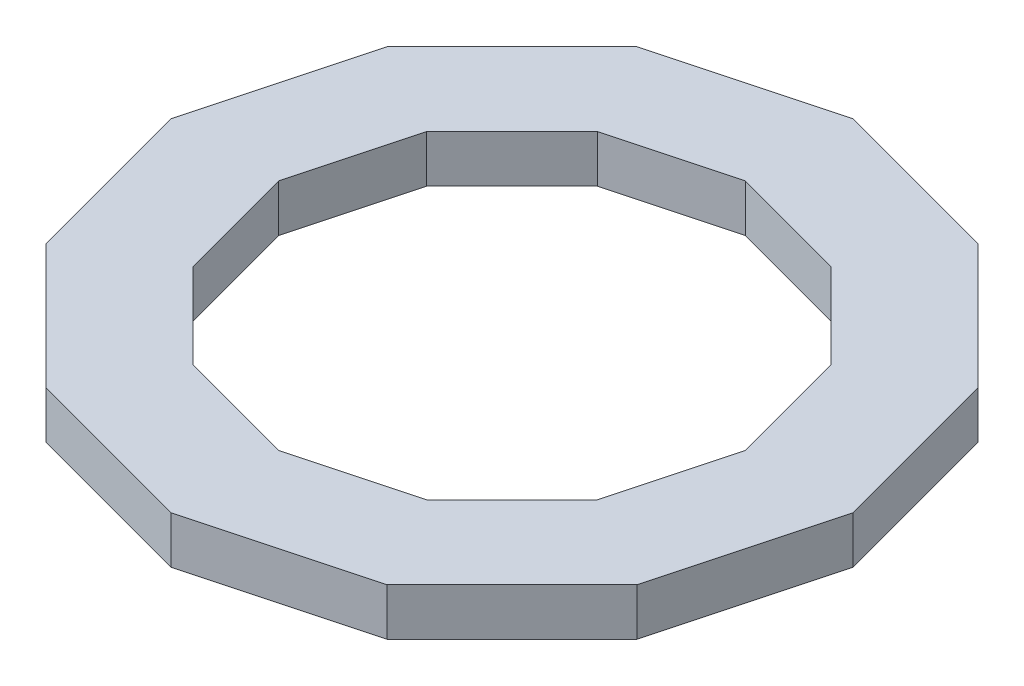
SolidWorks part; units mm, degrees
ref_plane "Front Plane" through (0, 0, 0) normal (0, 0, 1) x (1, 0, 0)
ref_plane "Top Plane" through (0, 0, 0) normal (0, 1, 0) x (1, 0, 0)
ref_plane "Right Plane" through (0, 0, 0) normal (1, 0, 0) x (0, 0, -1)
sketch "Sketch2" plane through (0, 0, 0) normal (0, 1, 0) x (1, 0, 0)
  line L0 (-137.3933, 0) -> (-94.0049, 0) construction
  line L1 (-137.3933, 0) -> (-118.9861, -68.6966)
  line L2 (-118.9861, -68.6966) -> (-68.6966, -118.9861)
  line L3 (-68.6966, -118.9861) -> (0, -137.3933)
  line L4 (0, -137.3933) -> (68.6966, -118.9861)
  line L5 (68.6966, -118.9861) -> (118.9861, -68.6966)
  line L6 (118.9861, -68.6966) -> (137.3933, 0)
  line L7 (137.3933, 0) -> (118.9861, 68.6966)
  line L8 (118.9861, 68.6966) -> (68.6966, 118.9861)
  line L9 (68.6966, 118.9861) -> (0, 137.3933)
  line L10 (0, 137.3933) -> (-68.6966, 118.9861)
  line L11 (-68.6966, 118.9861) -> (-118.9861, 68.6966)
  line L12 (-118.9861, 68.6966) -> (-137.3933, 0)
  line L13 (-94.0049, 0) -> (-81.4106, -47.0024)
  line L14 (-81.4106, -47.0024) -> (-47.0024, -81.4106)
  line L15 (-47.0024, -81.4106) -> (0, -94.0049)
  line L16 (0, -94.0049) -> (47.0024, -81.4106)
  line L17 (47.0024, -81.4106) -> (81.4106, -47.0024)
  line L18 (81.4106, -47.0024) -> (94.0049, 0)
  line L19 (94.0049, 0) -> (81.4106, 47.0024)
  line L20 (81.4106, 47.0024) -> (47.0024, 81.4106)
  line L21 (47.0024, 81.4106) -> (0, 94.0049)
  line L22 (0, 94.0049) -> (-47.0024, 81.4106)
  line L23 (-47.0024, 81.4106) -> (-81.4106, 47.0024)
  line L24 (-81.4106, 47.0024) -> (-94.0049, 0)
  line L25 (0, 0) -> (-94.0049, 0) construction
  circle A0 centre (0, 0) radius 132.7117 construction
  circle A1 centre (0, 0) radius 90.8017 construction
  dimension "D1" = 71.12
  dimension "D2" = 41.91
extrude "Boss-Extrude2" add sketch "Sketch2" along normal blind 19.05
